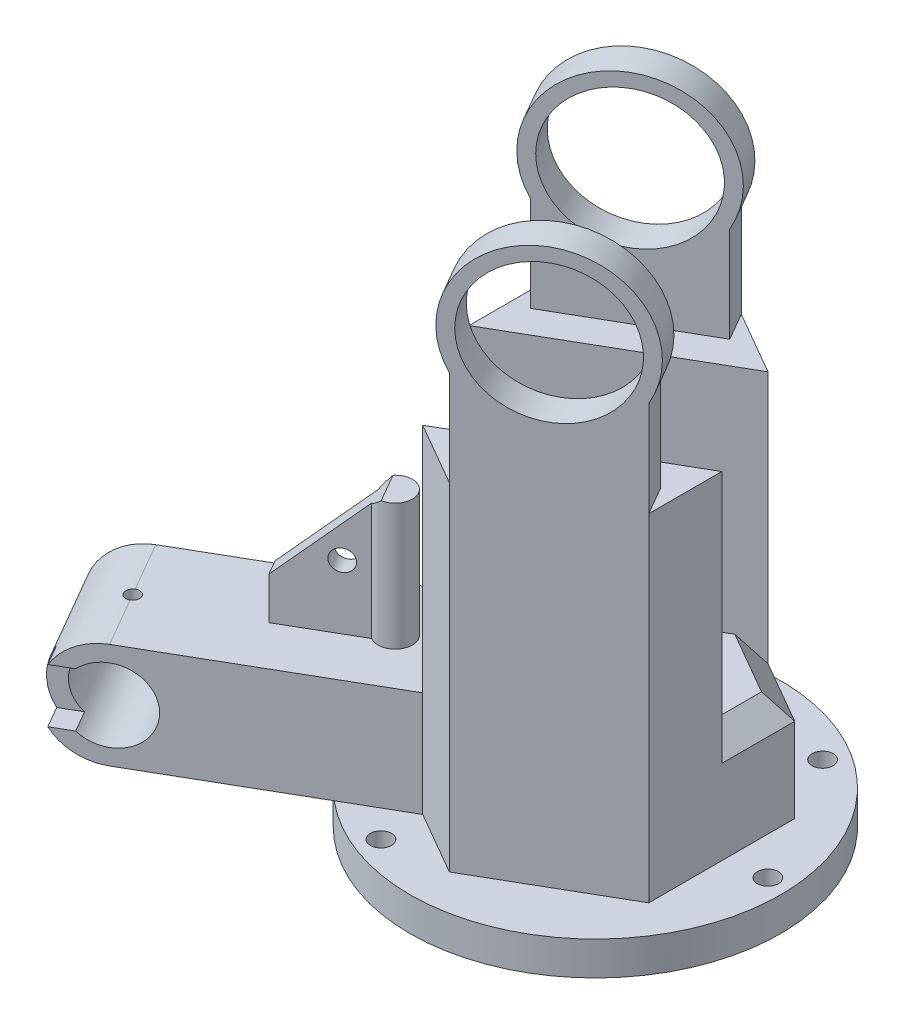
SolidWorks part; units mm, degrees
ref_plane "Front Plane" through (0, 0, 0) normal (0, 0, 1) x (1, 0, 0)
ref_plane "Top Plane" through (0, 0, 0) normal (0, 1, 0) x (1, 0, 0)
ref_plane "Right Plane" through (0, 0, 0) normal (1, 0, 0) x (0, 0, -1)
sketch "Sketch4" plane through (0, 0, 0) normal (0, 1, 0) x (1, 0, 0)
  circle A1 centre (0, 0) radius 55.88
  dimension "D2" = 111.76
extrude "Boss-Extrude2" add sketch "Sketch4" along normal blind 10.16
sketch "Sketch8" plane through (0, 10.16, 0) normal (0, 1, 0) x (1, 0, 0)
  line L1 (0, 43.9941) -> (-38.1, 21.997)
  line L2 (-38.1, 21.997) -> (-38.1, -21.997)
  line L3 (-38.1, -21.997) -> (0, -43.9941)
  line L4 (0, -43.9941) -> (38.1, -21.997)
  line L5 (38.1, -21.997) -> (38.1, 21.997)
  line L6 (38.1, 21.997) -> (0, 43.9941)
  circle A0 centre (0, 0) radius 38.1 construction
  dimension "D1" = 76.2
extrude "Boss-Extrude4" add sketch "Sketch8" along normal blind 101.6
sketch "Sketch9" plane through (-19.05, 0, -32.9956) normal (-0.5, 0, -0.866) x (-0.866, 0, 0.5)
  line L1 (21.997, 111.76) -> (-21.997, 111.76)
  line L2 (21.997, 111.76) -> (21.997, 140.5202)
  line L4 (-21.997, 111.76) -> (-21.997, 140.5202)
  arc A1 (21.997, 140.5202) -> (-21.997, 140.5202) centre (0, 152.4) ccw
  dimension "D2" = 50
extrude "Boss-Extrude5" add sketch "Sketch9" against normal blind 9.525
sketch "Sketch10" plane through (19.05, 0, 32.9956) normal (0.5, 0, 0.866) x (0.866, 0, -0.5)
  line L3 (-21.997, 111.76) -> (21.997, 111.76)
  line L4 (21.997, 111.76) -> (21.997, 140.5202)
  line L5 (-21.997, 140.5202) -> (-21.997, 111.76)
  line L6 (-21.997, 111.76) -> (21.997, 111.76)
  line L7 (21.997, 111.76) -> (21.997, 140.5202)
  line L8 (-21.997, 140.5202) -> (-21.997, 111.76)
  arc A1 (21.997, 140.5202) -> (-21.997, 140.5202) centre (0, 152.4) ccw
  arc A3 (21.997, 140.5202) -> (-21.997, 140.5202) centre (0, 152.4) ccw
  dimension "D1" = 0
extrude "Boss-Extrude6" add sketch "Sketch10" against normal blind 9.525
sketch "Sketch12" plane through (-19.05, 0, -32.9956) normal (-0.5, 0, -0.866) x (-0.866, 0, 0.5)
  circle A0 centre (0, 152.4) radius 20.828
  dimension "D1" = 41.656
extrude "Cut-Extrude4" cut sketch "Sketch12" against normal up to surface (76.2 mm away) up to face at (19.05, 93.6267, 32.9956)
sketch "Sketch13" plane through (-19.05, 0, 10.9985) normal (-0.866, 0, 0.5) x (0.5, 0, 0.866)
  line L0 (0, 111.76) -> (0, 10.16) construction
  line L1 (-19.05, 41.91) -> (19.05, 41.91)
  line L2 (-19.05, 41.91) -> (-19.05, 111.76)
  line L3 (-19.05, 111.76) -> (19.05, 111.76)
  line L4 (19.05, 41.91) -> (19.05, 111.76)
  line L5 (-19.05, 41.91) -> (19.05, 111.76) construction
  line L6 (-19.05, 111.76) -> (19.05, 41.91) construction
  line L7 (-38.1, 111.76) -> (0, 111.76) construction
  point P0 (0, 76.835)
  dimension "D1" = 69.85
  dimension "D2" = 0
  dimension "D3" = 38.1
extrude "Cut-Extrude5" cut sketch "Sketch13" against normal mid plane 152.4
sketch "Sketch14" plane through (-19.05, 0, -32.9956) normal (-0.5, 0, -0.866) x (-0.866, 0, 0.5)
  circle A0 centre (0, 124.7701) radius 3.8666
ref_plane "Plane1" through (0, 0, 0) normal (-0.5, 0, -0.866) x (-0.866, 0, 0.5)
sketch "Sketch17" plane through (0, 0, 0) normal (-0.5, 0, -0.866) x (-0.866, 0, 0.5)
  circle A0 centre (0, 152.4) radius 162.4584
  dimension "D1" = 324.9168
ref_plane "Plane3" through (38.1, 41.91, -21.997) normal (0, -1, 0) x (-1, 0, 0)
sketch "Sketch22" plane through (0, 0, 0) normal (-0.5, 0, -0.866) x (-0.866, 0, 0.5)
  line L5 (43.9941, 41.91) -> (102.101, 41.91)
  line L6 (102.101, 10.16) -> (43.9941, 10.16)
  line L8 (43.9941, 10.16) -> (21.997, 10.16)
  line L9 (21.997, 10.16) -> (21.997, 41.91)
  line L10 (21.997, 111.76) -> (21.997, 10.16) construction
  line L11 (21.997, 41.91) -> (43.9941, 41.91)
  arc A2 (102.101, 10.16) -> (102.101, 41.91) centre (102.101, 26.035) ccw
  circle A3 centre (0, 152.4) radius 162.4584 construction
  dimension "D1" = 31.75
ref_plane "Plane4" through (23.876, 0, 41.3544) normal (0.5, 0, 0.866) x (0.866, 0, -0.5)
extrude "Boss-Extrude10" add sketch "Sketch22" along normal mid plane 38.1
sketch "Sketch28" plane through (9.525, 0, 16.4978) normal (0.5, 0, 0.866) x (0.866, 0, -0.5)
  circle A0 centre (-102.101, 26.035) radius 11.049
  dimension "D1" = 22.098
extrude "Cut-Extrude9" cut sketch "Sketch28" against normal up to surface (38.1 mm away) up to face at (-68.1724, 22.86, 17.3623)
sketch "Sketch29" plane through (9.525, 0, 16.4978) normal (0.5, 0, 0.866) x (0.866, 0, -0.5)
  line L1 (-104.2944, 17.907) -> (-122.0056, 17.907)
  line L2 (-104.2944, 17.907) -> (-104.2944, 34.163)
  line L3 (-104.2944, 34.163) -> (-122.0056, 34.163)
  line L4 (-122.0056, 17.907) -> (-122.0056, 34.163)
  line L5 (-104.2944, 17.907) -> (-122.0056, 34.163) construction
  line L6 (-104.2944, 34.163) -> (-122.0056, 17.907) construction
  circle A0 centre (-102.101, 26.035) radius 11.049 construction
  arc A1 (-102.101, 41.91) -> (-102.101, 10.16) centre (-102.101, 26.035) ccw construction
  circle A2 centre (-102.101, 26.035) radius 11.049
  circle A3 centre (-102.101, 26.035) radius 11.049
  arc A4 (-102.101, 41.91) -> (-102.101, 10.16) centre (-102.101, 26.035) ccw
  point P0 (-113.15, 26.035)
  circle M3 centre (-102.101, 26.035) radius 11.049
  arc M7 (-102.101, 41.91) -> (-102.101, 10.16) centre (-102.101, 26.035) ccw
  dimension "D1" = 16.256
  dimension "D2" = 0
extrude "Cut-Extrude10" cut sketch "Sketch29" against normal blind 7.366 contours L3 L1 M3 M7
chamfer "Chamfer1" distance 6.35 angle 45 2 edges at (38.1, 41.91, -10.9985) (28.575, 41.91, -27.4963)
sketch "Sketch30" plane through (0, 41.91, 0) normal (0, 1, 0) x (1, 0, 0)
  line L0 (-97.9471, -34.5527) -> (-78.8971, -67.5483) construction
  circle A0 centre (-88.4221, -51.0505) radius 2.1
  dimension "D1" = 4.2
extrude "Cut-Extrude11" cut sketch "Sketch30" against normal blind 7.366
sketch "Sketch31" plane through (0, 10.16, 0) normal (0, 1, 0) x (1, 0, 0)
  circle A0 centre (0, 0) radius 49.53 construction
  circle A4 centre (-49.089, 6.5948) radius 3.175
  circle A5 centre (26.9253, 41.5722) radius 3.175
  dimension "D1" = 6.35
  dimension "D2" = 99.06
  dimension "D3" = 6.35
extrude "Cut-Extrude12" cut sketch "Sketch31" against normal through all
mirror "Mirror1" about plane through (0, 0, 0) normal (-0.5, 0, -0.866) of "Cut-Extrude12"
sketch "Sketch33" plane through (0, 41.91, 0) normal (0, 1, 0) x (1, 0, 0)
  line L0 (140.6931, 81.2292) -> (-140.6931, -81.2292) construction
  line L5 (-43.4119, -22.0798) -> (-63.0924, -33.4424)
  line L6 (-63.0924, -33.4424) -> (-61.8003, -35.6804)
  line L7 (-61.8003, -35.6804) -> (-60.5427, -37.8586)
  line L8 (-60.5427, -37.8586) -> (-40.9154, -26.5041)
  arc A0 (-40.9154, -26.5041) -> (-43.4119, -22.0798) centre (-38.2434, -22.0798) ccw
extrude "Boss-Extrude11" add sketch "Sketch33" along normal blind 38.1
chamfer "Chamfer2" distance 25.4 angle 45 1 edges at (-61.8176, 80.01, 35.6505)
sketch "Sketch34" plane through (-1.2921, 0, -2.238) normal (-0.5, 0, -0.866) x (-0.866, 0, 0.5)
  circle A0 centre (55.1848, 61.1591) radius 3.175
  dimension "D1" = 6.35
extrude "Cut-Extrude13" cut sketch "Sketch34" against normal up to surface (5.0881 mm away) up to face at (-50.7291, 53.9288, 32.1813)
